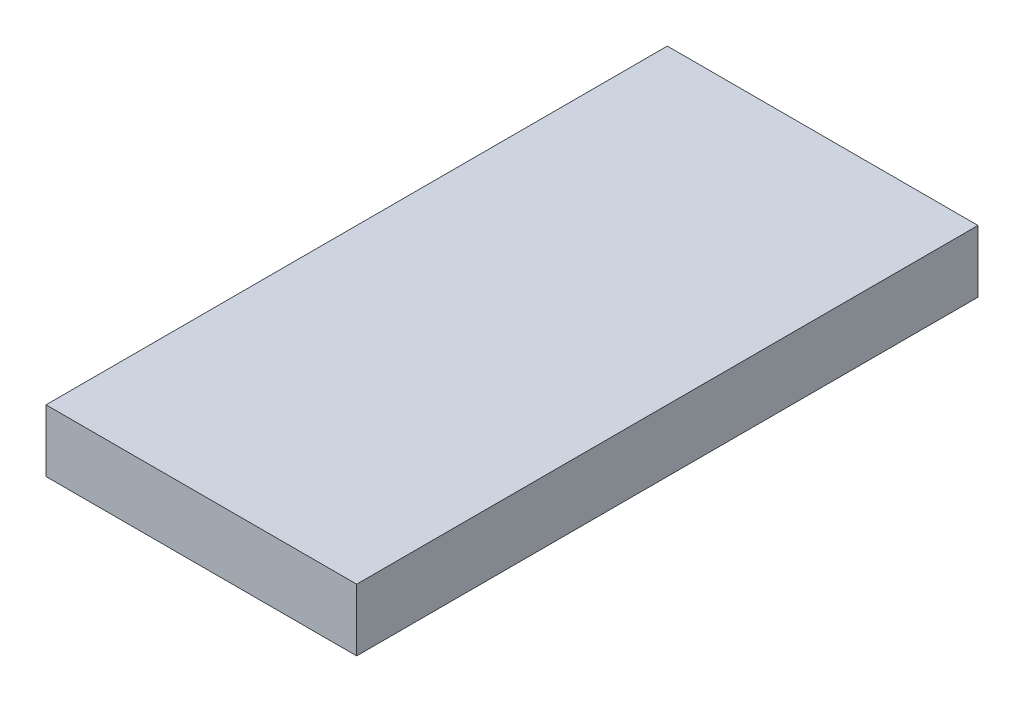
SolidWorks part; units mm, degrees
ref_plane "Спереди" through (0, 0, 0) normal (0, 0, 1) x (1, 0, 0)
ref_plane "Сверху" through (0, 0, 0) normal (0, 1, 0) x (1, 0, 0)
ref_plane "Справа" through (0, 0, 0) normal (1, 0, 0) x (0, 0, -1)
sketch "Эскиз1" plane through (0, 0, 0) normal (0, 1, 0) x (1, 0, 0)
  line L1 (-10, -20) -> (10, -20)
  line L2 (-10, -20) -> (-10, 20)
  line L3 (-10, 20) -> (10, 20)
  line L4 (10, -20) -> (10, 20)
  line L5 (0, 20) -> (0, -20) construction
  line L6 (-10, 0) -> (10, 0) construction
  point P0 (0, 0)
  dimension "D1" = 20
  dimension "D2" = 40
extrude "Бобышка-Вытянуть1" add sketch "Эскиз1" along normal mid plane 4
